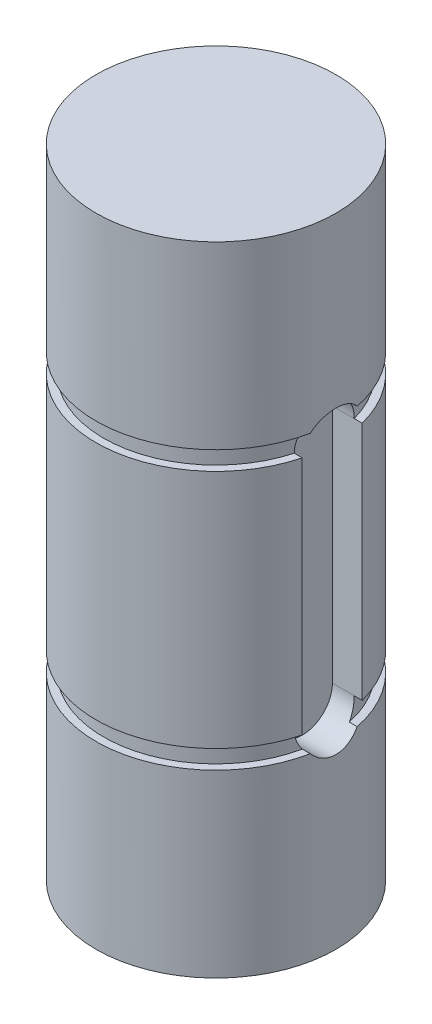
SolidWorks part; units mm, degrees
ref_plane "Front Plane" through (0, 0, 0) normal (0, 0, 1) x (1, 0, 0)
ref_plane "Top Plane" through (0, 0, 0) normal (0, 1, 0) x (1, 0, 0)
ref_plane "Right Plane" through (0, 0, 0) normal (1, 0, 0) x (0, 0, -1)
sketch "Sketch1" plane through (0, 0, 0) normal (0, 1, 0) x (1, 0, 0)
  circle A0 centre (0, 0) radius 2.5
extrude "Boss-Extrude1" add sketch "Sketch1" along normal blind 13.28 contours A0
sketch "Sketch2" plane through (0, 0, 0) normal (1, 0, 0) x (0, 0, -1)
  line L0 (2.5, 13.28) -> (-2.5, 13.28) construction
  line L1 (-8.787, 9.53) -> (-2.34, 9.53)
  line L2 (-8.787, 9.53) -> (-8.787, 9.14)
  line L3 (-8.787, 9.14) -> (-2.34, 9.14)
  line L4 (-2.34, 9.53) -> (-2.34, 9.14)
  line L5 (-2.5, 13.28) -> (-2.5, 0) construction
  line L6 (0, 10.1945) -> (0, 7.0995) construction
  dimension "D1" = 3.75
  dimension "D2" = 0.39
  dimension "D3" = 0.16
revolve "Cut-Revolve1" cut sketch "Sketch2" angle 360 about L6
sketch "Sketch3" plane through (0, 0, 0) normal (1, 0, 0) x (0, 0, -1)
  line L0 (2.5, 9.14) -> (-2.5, 9.14) construction
  line L1 (-8.9507, 4.14) -> (-2.34, 4.14)
  line L2 (-8.9507, 4.14) -> (-8.9507, 3.75)
  line L3 (-8.9507, 3.75) -> (-2.34, 3.75)
  line L4 (-2.34, 4.14) -> (-2.34, 3.75)
  line L5 (-2.5, 9.14) -> (-2.5, 0) construction
  line L6 (0, 6.0781) -> (0, 3.3193) construction
  dimension "D1" = 5
  dimension "D2" = 0.39
  dimension "D3" = 0.16
revolve "Cut-Revolve2" cut sketch "Sketch3" angle 360 about L6
ref_plane "Plane1" through (2.5, 0, 0) normal (1, 0, 0) x (0, 0, -1)
sketch "Sketch4" plane through (2.5, 0, 0) normal (1, 0, 0) x (0, 0, -1)
  line L0 (0, 9.14) -> (0, 4.14) construction
  line L1 (2.5, 9.14) -> (-2.5, 9.14) construction
  line L2 (-2.34, 4.14) -> (2.34, 4.14) construction
  line L3 (0.625, 9.14) -> (0.625, 4.14)
  line L4 (-0.625, 9.14) -> (-0.625, 4.14)
  arc A0 (0.625, 9.14) -> (-0.625, 9.14) centre (0, 9.14) ccw
  arc A1 (-0.625, 4.14) -> (0.625, 4.14) centre (0, 4.14) ccw
  point P6 (0, 6.64)
  dimension "D1" = 1.25
extrude "Cut-Extrude1" cut sketch "Sketch4" against normal blind 0.7 contours L4 A1 L3 A0
